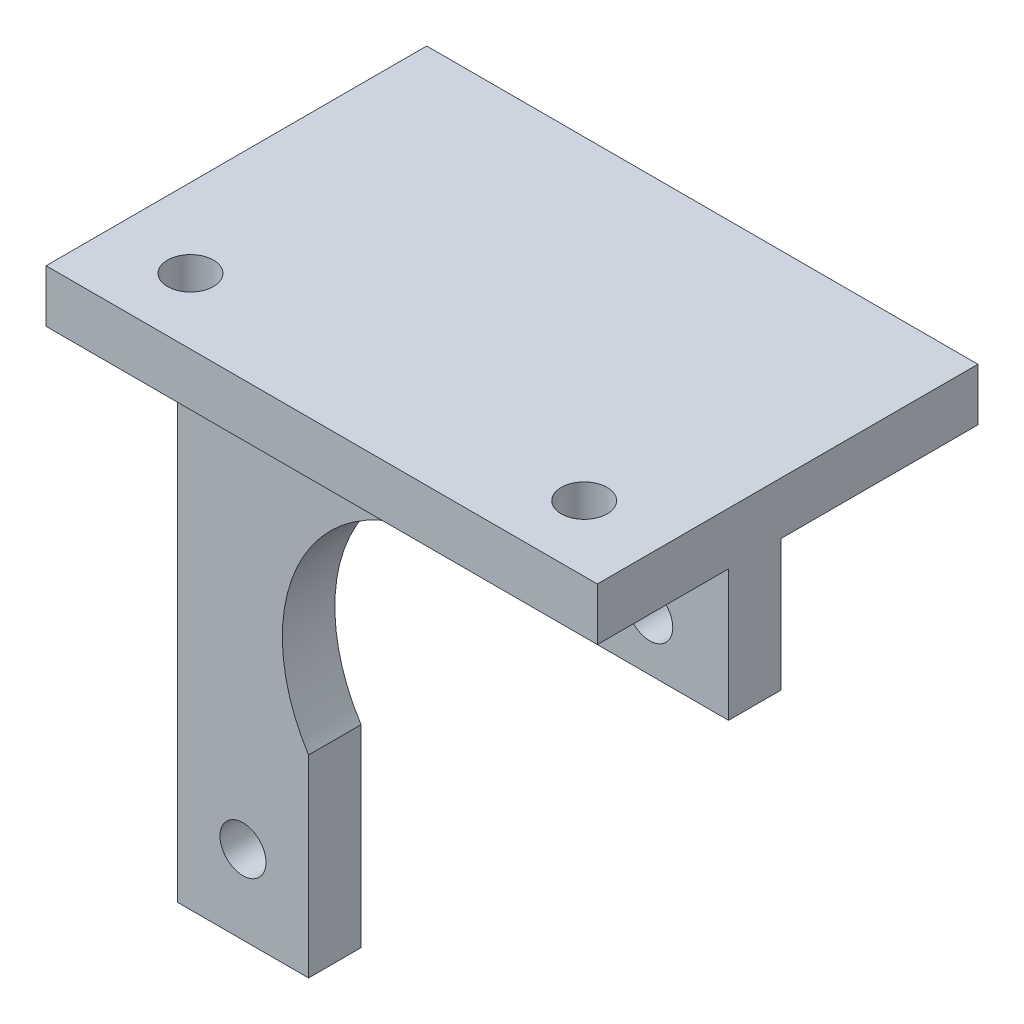
SolidWorks part; units mm, degrees
ref_plane "Plano frontal" through (0, 0, 0) normal (0, 0, 1) x (1, 0, 0)
ref_plane "Plano superior" through (0, 0, 0) normal (0, 1, 0) x (1, 0, 0)
ref_plane "Plano direito" through (0, 0, 0) normal (1, 0, 0) x (0, 0, -1)
sketch "Esboço1" plane through (0, 0, 0) normal (0, 0, 1) x (1, 0, 0)
  line L0 (15.5, 15.5) -> (-15.5, 15.5) construction
  line L1 (-15.5, -15.5) -> (-15.5, 15.5) construction
  line L2 (-20.5, -21.5) -> (-20.5, 21.5)
  line L3 (-20.5, 21.5) -> (21.5, 21.5)
  line L4 (21.5, 21.5) -> (21.5, 11.5)
  line L5 (21.5, 11.5) -> (4.899, 11.5)
  line L6 (-10.5, -6.7823) -> (-10.5, -21.5)
  line L7 (-10.5, -21.5) -> (-20.5, -21.5)
  arc A0 (4.899, 11.5) -> (-10.5, -6.7823) centre (0, 0) ccw
  circle A1 centre (-15.5, 15.5) radius 1.75
  circle A2 centre (15.5, 15.5) radius 1.75
  circle A3 centre (-15.5, -15.5) radius 1.75
  point P9 (0, 15.5)
  point P11 (-15.5, 0)
  point P18 (-15.5, -21.5)
  point P19 (0, 12.3843)
  point P20 (0, 12.3843)
  point P21 (0, 7.7746)
  point P22 (5.9733, 10.9804)
  point P23 (21.6244, 10.9804)
  point P24 (-12.5, 0)
  point P25 (-11.2974, -5.3497)
  point P27 (-12.424, -22)
  point P28 (5.9372, 11)
  dimension "D2" = 25
  dimension "D3" = 3.5
  dimension "D1" = 31
  dimension "D4" = 10
  dimension "D5" = 42
  dimension "D6" = 6
extrude "Ressalto-extrusão1" add sketch "Esboço1" along normal blind 4
sketch "Esboço2" plane through (0, 21.5, 0) normal (0, 1, 0) x (1, 0, 0)
  line L0 (-20.5, -4) -> (-20.5, 0) construction
  line L1 (-20.5, 15) -> (21.5, 15)
  line L2 (-20.5, 15) -> (-20.5, -14)
  line L3 (-20.5, -14) -> (21.5, -14)
  line L4 (21.5, 15) -> (21.5, -14)
  line L5 (21.5, -4) -> (21.5, 0) construction
  line L6 (0.5, -14) -> (0.5, -4) construction
  line L7 (21.5, -4) -> (-20.5, -4) construction
  line L8 (21.5, 0) -> (-20.5, 0) construction
  circle A0 centre (-14.5, -9) radius 1.75
  circle A1 centre (15.5, -9) radius 1.75
  point P13 (0.5, -4)
  point P14 (0.5, -9)
  dimension "D1" = 3.5
  dimension "D2" = 30
  dimension "D3" = 10
  dimension "D4" = 15
extrude "Ressalto-extrusão2" add sketch "Esboço2" along normal blind 4
